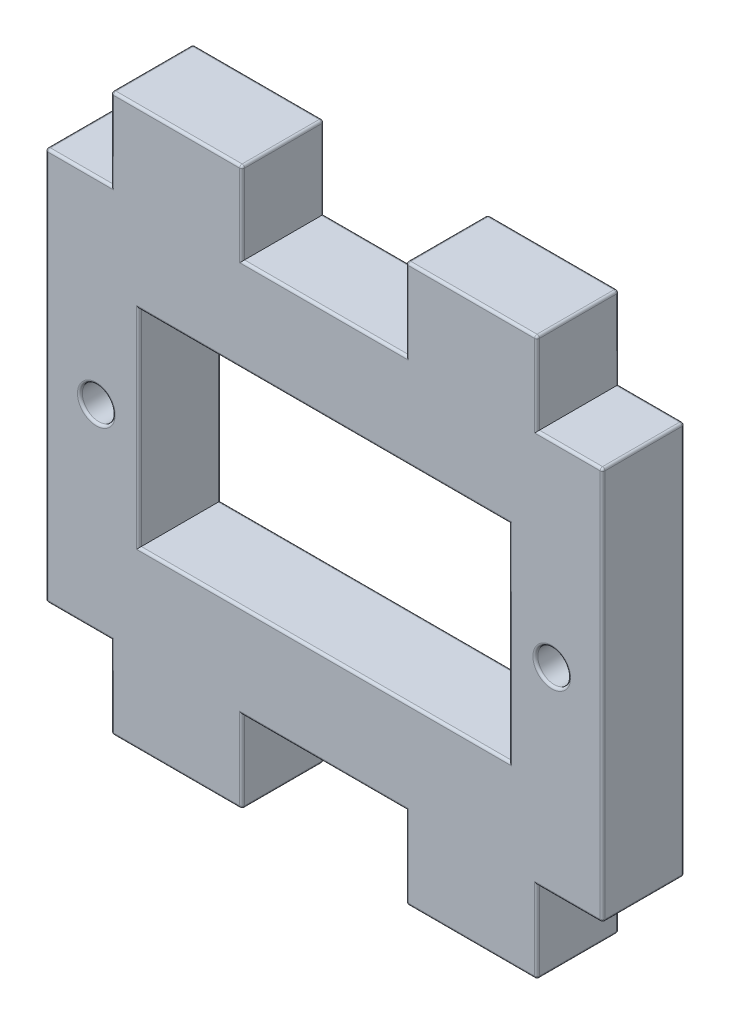
SolidWorks part; units mm, degrees
ref_plane "Front Plane" through (0, 0, 0) normal (0, 0, 1) x (1, 0, 0)
ref_plane "Top Plane" through (0, 0, 0) normal (0, 1, 0) x (1, 0, 0)
ref_plane "Right Plane" through (0, 0, 0) normal (1, 0, 0) x (0, 0, -1)
sketch "Sketch1" plane through (0, 0, 0) normal (0, 0, 1) x (1, 0, 0)
  line L0 (-19.4134, 0) -> (0, 0) construction
  line L1 (-11.3, -6.3) -> (11.3, -6.3)
  line L2 (-11.3, -6.3) -> (-11.3, 6.3)
  line L3 (-11.3, 6.3) -> (11.3, 6.3)
  line L4 (11.3, -6.3) -> (11.3, 6.3)
  line L5 (-11.3, -6.3) -> (11.3, 6.3) construction
  line L6 (-11.3, 6.3) -> (11.3, -6.3) construction
  line L13 (-13, 17) -> (-5, 17)
  line L14 (-13, 17) -> (-13, 12)
  line L15 (-13, 12) -> (-5, 12)
  line L16 (-5, 17) -> (-5, 12)
  line L19 (0, 0) -> (0, 6.3) construction
  line L20 (13, 12) -> (5, 12)
  line L21 (5, 17) -> (5, 12)
  line L22 (13, 17) -> (5, 17)
  line L23 (13, 17) -> (13, 12)
  line L24 (13, -17) -> (13, -12)
  line L25 (13, -17) -> (5, -17)
  line L26 (5, -17) -> (5, -12)
  line L27 (13, -12) -> (5, -12)
  line L28 (-13, -12) -> (-5, -12)
  line L29 (-5, -17) -> (-5, -12)
  line L30 (-13, -17) -> (-5, -17)
  line L31 (-13, -17) -> (-13, -12)
  line L32 (-17, -12) -> (-17, 12)
  line L33 (-17, 12) -> (17, 12)
  line L34 (17, -12) -> (17, 12)
  line L35 (-17, -12) -> (17, -12)
  circle A0 centre (-13.9, 0) radius 1
  circle A1 centre (13.9, 0) radius 1
  point P0 (0, 0)
  point P6 (0, 0)
  dimension "D7" = 2
  dimension "D1" = 12.6
  dimension "D2" = 22.6
  dimension "D3" = 5.7
  dimension "D4" = 5
  dimension "D5" = 4
  dimension "D6" = 8
  dimension "D8" = 2.6
  dimension "D9" = 24
  dimension "D10" = 10
extrude "Boss-Extrude1" add sketch "Sketch1" along normal mid plane 5
fillet "Fillet1" radius 0.15 64 edges at (-15, 12, 2.5) (-13, 14.5, 2.5) (-9, 17, 2.5) (-5, 14.5, 2.5) (0, 12, 2.5) (5, 14.5, 2.5) (9, 17, 2.5) (13, 14.5, 2.5) (15, 12, 2.5) (17, 0, 2.5) (15, -12, 2.5) (13, -14.5, 2.5) (9, -17, 2.5) (5, -14.5, 2.5) (0, -12, 2.5) (-5, -14.5, 2.5) (-9, -17, 2.5) (-13, -14.5, 2.5) (-15, -12, 2.5) (-17, 0, 2.5) (0, 6.3, 2.5) (-11.3, 0, 2.5) (0, -6.3, 2.5) (11.3, 0, 2.5) (-12.9, 0, 2.5) (14.9, 0, 2.5) (-17, 0, -2.5) (-15, -12, -2.5) (-13, -14.5, -2.5) (-9, -17, -2.5) (-5, -14.5, -2.5) (0, -12, -2.5) (5, -14.5, -2.5) (9, -17, -2.5) (13, -14.5, -2.5) (15, -12, -2.5) (17, 0, -2.5) (15, 12, -2.5) (13, 14.5, -2.5) (9, 17, -2.5) (5, 14.5, -2.5) (0, 12, -2.5) (-5, 14.5, -2.5) (-9, 17, -2.5) (-13, 14.5, -2.5) (-15, 12, -2.5) (11.3, 0, -2.5) (0, -6.3, -2.5) (-11.3, 0, -2.5) (0, 6.3, -2.5) (-12.9, 0, -2.5) (14.9, 0, -2.5) (-17, 12, 0) (-13, 17, 0) (5, 17, 0) (13, 17, 0) (17, 12, 0) (17, -12, 0) (13, -17, 0) (5, -17, 0) (-5, -17, 0) (-13, -17, 0) (-17, -12, 0) (-5, 17, 0)
